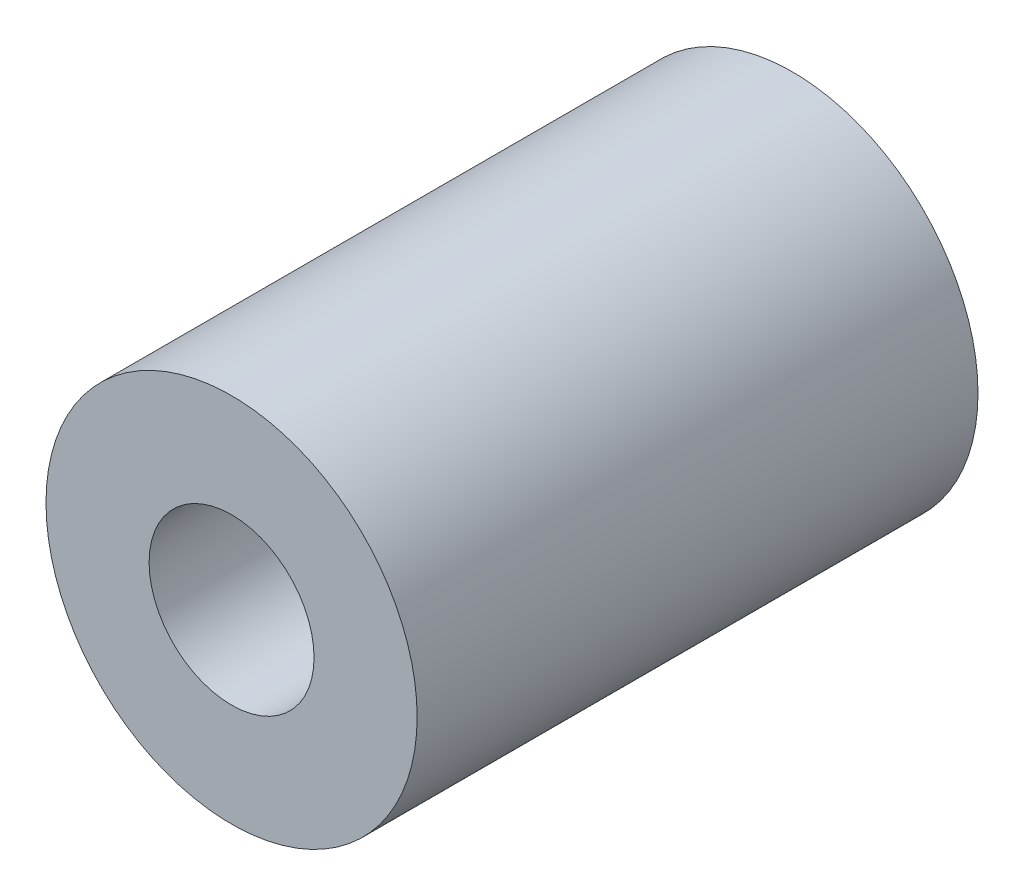
SolidWorks part; units mm, degrees
material "1.1193 (C45G)"
ref_plane "Alzado" through (0, 0, 0) normal (0, 0, 1) x (1, 0, 0)
ref_plane "Planta" through (0, 0, 0) normal (0, 1, 0) x (1, 0, 0)
ref_plane "Vista lateral" through (0, 0, 0) normal (1, 0, 0) x (0, 0, -1)
sketch "Croquis1" plane through (0, 0, 0) normal (0, 0, 1) x (1, 0, 0)
  circle A0 centre (0, 0) radius 1
  circle A1 centre (0, 0) radius 2.25
  dimension "D1" = 2
  dimension "D2" = 4.5
extrude "Saliente-Extruir1" add sketch "Croquis1" along normal blind 6.8
